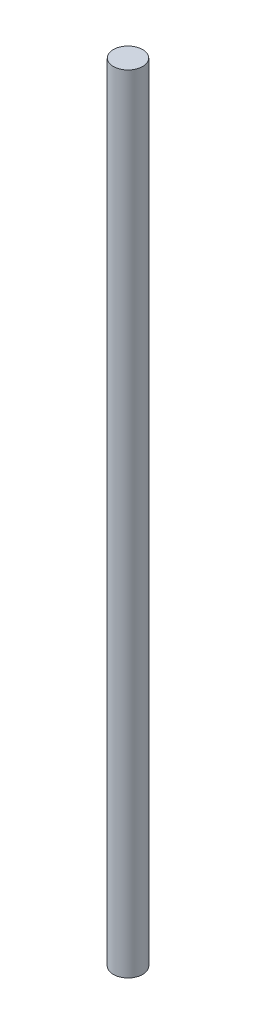
SolidWorks part; units mm, degrees
ref_plane "Front Plane" through (0, 0, 0) normal (0, 0, 1) x (1, 0, 0)
ref_plane "Top Plane" through (0, 0, 0) normal (0, 1, 0) x (1, 0, 0)
ref_plane "Right Plane" through (0, 0, 0) normal (1, 0, 0) x (0, 0, -1)
sketch "Sketch1" plane through (0, 0, 0) normal (0, 1, 0) x (1, 0, 0)
  circle A0 centre (0, 0) radius 0.9487
  dimension "D1" = 1.8974
extrude "Boss-Extrude1" add sketch "Sketch1" along normal blind 50.8
